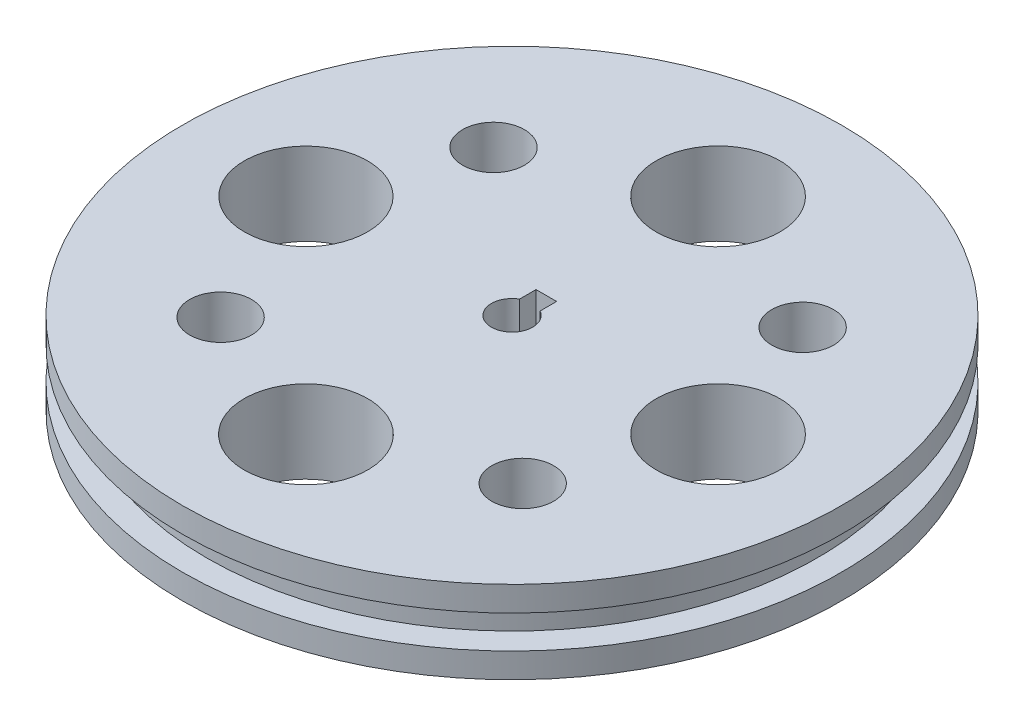
SolidWorks part; units mm, degrees
ref_plane "Front Plane" through (0, 0, 0) normal (0, 0, 1) x (1, 0, 0)
ref_plane "Top Plane" through (0, 0, 0) normal (0, 1, 0) x (1, 0, 0)
ref_plane "Right Plane" through (0, 0, 0) normal (1, 0, 0) x (0, 0, -1)
sketch "Sketch1" plane through (0, 0, 0) normal (0, 0, 1) x (1, 0, 0)
  line L0 (0, 0) -> (101.5589, 0)
  line L1 (101.5589, 0) -> (101.5589, 7.6582)
  line L2 (101.5589, 7.6582) -> (94.0186, 7.6582)
  line L3 (94.0186, 7.6582) -> (94.0186, 17.7905)
  line L4 (94.0186, 17.7905) -> (101.5589, 17.7905)
  line L5 (101.5589, 17.7905) -> (101.5589, 25.4486)
  line L6 (101.5589, 25.4486) -> (0, 25.4486)
  line L7 (0, 25.4486) -> (0, 0)
  point P9 (101.5589, 3.8291)
  point P10 (94.0186, 12.7243)
  dimension "D1" = 25.4486
  dimension "D2" = 101.5589
  dimension "D3" = 7.6582
  dimension "D4" = 7.5403
  dimension "D5" = 7.5403
revolve "Revolve1" add sketch "Sketch1" angle 360 about L7
sketch "Sketch3" plane through (0, 25.4486, 0) normal (0, 1, 0) x (1, 0, 0)
  line L1 (-3.175, 10.5809) -> (3.175, 10.5809)
  line L2 (-3.175, 10.5809) -> (-3.175, 0.4209)
  line L3 (-0.0959, 0.4209) -> (3.175, 0.4209)
  line L4 (-3.175, 0.4209) -> (3.175, 0.4209)
  line L5 (3.175, 10.5809) -> (3.175, 0.4209)
  circle A0 centre (0, 0) radius 63.5
  circle A1 centre (0, 63.5) radius 19.05
  circle A2 centre (0, -63.5) radius 19.05
  circle A3 centre (63.5, 0) radius 19.05
  circle A4 centre (-63.5, 0) radius 18.9883
  circle A5 centre (-47.6599, 41.9617) radius 9.525
  circle A6 centre (47.9972, 41.5755) radius 9.525
  circle A7 centre (-44.3867, -45.41) radius 9.525
  circle A8 centre (46.5215, -43.2204) radius 9.525
  circle A9 centre (0, 0) radius 6.35
  dimension "D1" = 127
  dimension "D2" = 37.9767
  dimension "D3" = 38.1
  dimension "D4" = 38.1
  dimension "D5" = 38.1
  dimension "D6" = 19.05
  dimension "D7" = 19.05
  dimension "D8" = 19.05
  dimension "D9" = 19.05
  dimension "D10" = 19.05
  dimension "D11" = 12.7
  dimension "D12" = 10.16
  dimension "D13" = 6.35
  dimension "D14" = 3.175
extrude "Cut-Extrude2" cut sketch "Sketch3" against normal through all contours A0 A7 | A0 A2 | A0 A2 | A0 A8 | A1 | A5 | L4 L2 L1 L5 | A9 | A6 | A3 | A4
